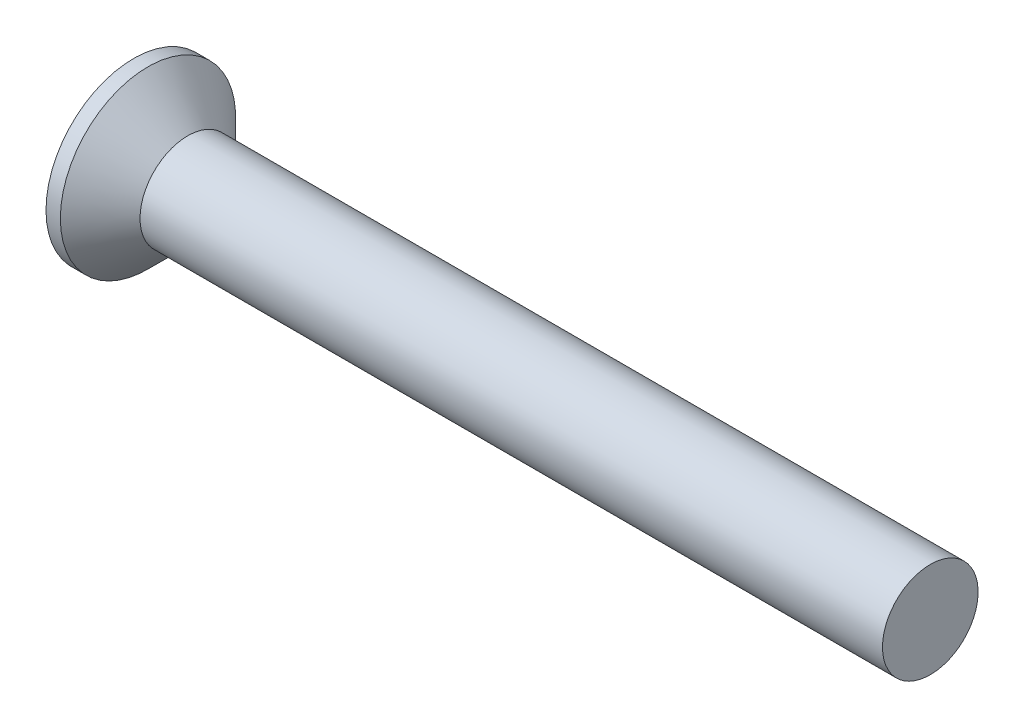
SolidWorks part; units mm, degrees
revolve "Base-Revolve" add sketch "BodySke" angle 360 about L5
sketch "BodySke" plane through (0, 0, 0) normal (0, 0, 1) x (1, 0, 0)
  line L0 (0, 0) -> (0, 2.75)
  line L1 (0, 2.75) -> (0.45, 2.75)
  line L2 (1.7, 1.5) -> (25, 1.5)
  line L3 (25, 1.5) -> (25, 0)
  line L4 (25, 0) -> (0, 0)
  line L5 (-6.35, 0) -> (82.55, 0) construction
  line L6 (1.7, -1.5) -> (25, -1.5) construction
  line L7 (0.45, -2.75) -> (1.7, -1.5) construction
  line L8 (0.45, 2.75) -> (1.7, 1.5)
  line L9 (0, -2.75) -> (0.45, -2.75) construction
  line L10 (2.2, 3.0875) -> (2.2, -6.4375) construction
  line L11 (0, 6.35) -> (0, -3.175) construction
  dimension "Diameter" = 3
  dimension "Head_ht" = 1.7
  dimension "Head_dia" = 5.5
  dimension "Head_ang" = 90
  dimension "D6" = 0.45
  dimension "Advance" = 0.5
cosmetic thread "ThreadCosmetic" [suppressed] parameters "Thread_length"=22.8, "Thread_minor"=2.439
extrude "Slot" [suppressed] cut sketch "Sketch2" against normal blind 0.9
sketch "Sketch2" plane through (0, 0, 0) normal (-1, 0, 0) x (0, 0, 1)
  line L0 (-2.75, -0.5) -> (2.75, -0.5)
  line L1 (-2.75, -0.5) -> (-2.75, 0.5)
  line L2 (2.75, 0.5) -> (-2.75, 0.5)
  line L3 (2.75, 0.5) -> (2.75, -0.5)
  dimension "Slot_width" = 1
  dimension "D1" = 0.5
  dimension "D2" = 5.5
  dimension "D3" = 2.75
ref_plane "Plane1" through (0, 0, 0) normal (0, 0, 1) x (1, 0, 0)
ref_plane "Plane2" through (0, 0, 0) normal (0, 1, 0) x (1, 0, 0)
ref_plane "Plane3" through (0, 0, 0) normal (1, 0, 0) x (0, 0, -1)
sketch "Sketch3" plane through (0, 0, 0) normal (-1, 0, 0) x (0, 0, 1)
  line L0 (-0.395, 1.55) -> (0.395, 1.55)
  line L1 (0.395, 1.55) -> (0.395, -1.55)
  line L2 (0.395, -1.55) -> (-0.395, -1.55)
  line L3 (-0.395, -1.55) -> (-0.395, 1.55)
  dimension "Cross_dia" = 3.1
  dimension "Cross_width" = 0.79
  dimension "D1" = 1.55
  dimension "D2" = 0.395
ref_plane "Plane4" through (2.08, 0, 0) normal (-1, 0, 0) x (0, 0, 1)
sketch "Sketch4" plane through (2.08, 0, 0) normal (-1, 0, 0) x (0, 0, 1)
  line L0 (-0.1975, 0.1975) -> (0.1975, 0.1975)
  line L3 (0.1975, 0.1975) -> (0.1975, -0.1975)
  line L4 (0.1975, -0.1975) -> (-0.1975, -0.1975)
  line L5 (-0.1975, -0.1975) -> (-0.1975, 0.1975)
  dimension "D2" = 0.395
  dimension "D1" = 0.395
  dimension "D3" = 0.1975
  dimension "D4" = 0.1975
loft "Cross" cut profiles "Sketch3", "Sketch4"
pattern_circular "CirPattern1" count 2 every 90 about axis through (0, 0, 0) along (1, 0, 0) of "Cross"
sketch "ThdSchSke" plane through (0, 0, 0) normal (0, 0, 1) x (1, 0, 0)
  line L0 (2.2, -1.2195) -> (2.0036, -1.5)
  line L1 (2.2, -1.2195) -> (2.3964, -1.5)
  line L2 (2.3964, -1.5) -> (2.3964, -1.875)
  line L3 (-3.175, 0) -> (5.1513, 0) construction
  line L5 (2.3964, -1.875) -> (2.0036, -1.875)
  line L6 (2.0036, -1.875) -> (2.0036, -1.5)
  line L7 (0, 2.75) -> (0, -2.75) construction
  dimension "Diameter" = 3
  dimension "Thread_minor" = 2.439
  dimension "Start" = 2.2
revolve "ThreadSchematic" [suppressed] cut sketch "ThdSchSke" angle 360 about L3
pattern_linear "ThdSchPat" [suppressed]
equation "\"D1@Sketch3\" = \"Cross_dia@Sketch3\" / 2"
equation "\"D2@Sketch3\" = \"Cross_width@Sketch3\" / 2"
equation "\"D1@Sketch4\" = \"Cross_width@Sketch3\" *.5"
equation "\"D2@Sketch4\" = \"D1@Sketch4\""
equation "\"D4@Sketch4\" = \"D2@Sketch4\" / 2"
equation "\"D3@Sketch4\" = \"D1@Sketch4\" / 2"
equation "\"D1@Sketch2\" = \"Slot_width@Sketch2\" / 2"
equation "\"D2@Sketch2\" = \"Head_dia@BodySke\""
equation "\"D3@Sketch2\" = \"D2@Sketch2\" / 2"
equation "\"Thread_length@ThreadCosmetic\" = ((sgn( (\"Length@BodySke\" - \"Advance@BodySke\" - \"Head_ht@BodySke\" ) - \"Thread_nom@BodySke\" )-1)*( (\"Length@BodySke\" - \"Advance@BodySke\" - \"Head_ht@BodySke\" ) - \"Thread_nom@BodySke\" ))/-2+ \"Thread_nom@BodySke\""
equation "\"Thread_minor@ThdSchSke\" = \"Thread_minor@ThreadCosmetic\""
equation "\"Diameter@ThdSchSke\" = \"Diameter@BodySke\""
equation "\"Overcut@ThdSchSke\" = \"Diameter@BodySke\" * 1.25"
equation "\"Start@ThdSchSke\" = 0.000001 + \"Length@BodySke\" - \"Thread_length@ThreadCosmetic\"  '---Countersunk---"
equation "\"Num_threads@ThdSchPat\" = int( \"Thread_length@ThreadCosmetic\" / \"Advance@BodySke\" + 0.999 )  + 1"
equation "\"Advance@ThdSchPat\" = \"Thread_length@ThreadCosmetic\" /  (\"Num_threads@ThdSchPat\" - 1) 'relax it"
